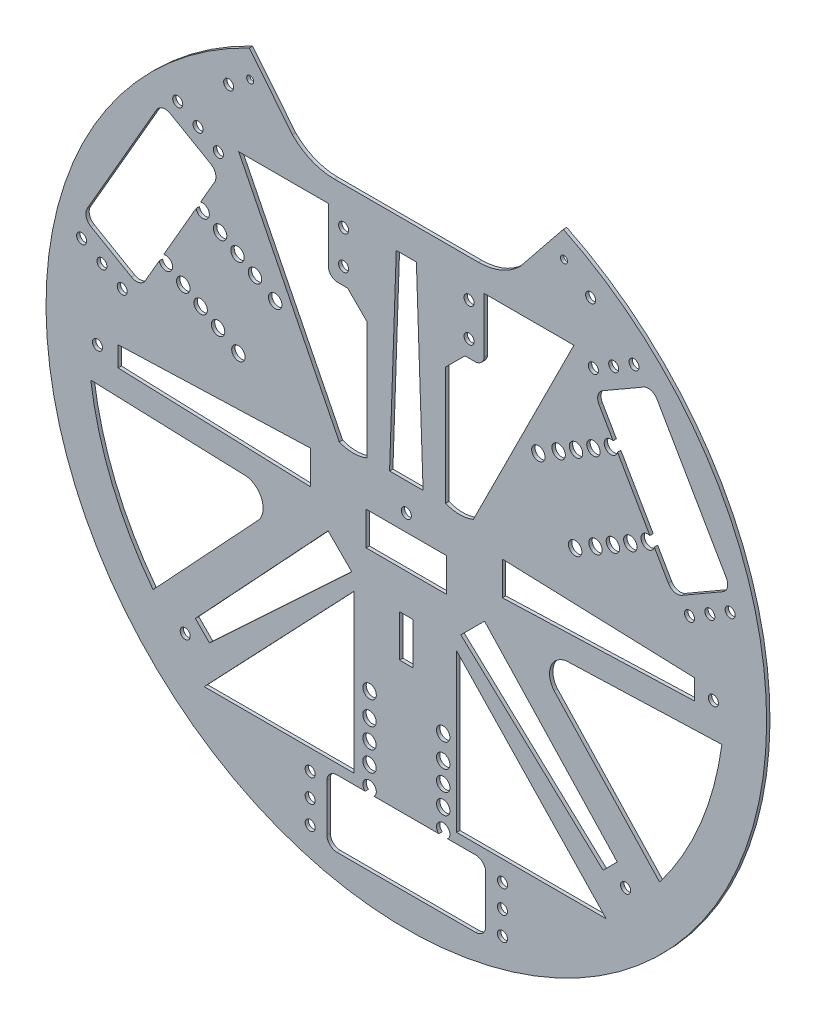
SolidWorks part; units mm, degrees
ref_plane "Alzado" through (0, 0, 0) normal (0, 0, 1) x (1, 0, 0)
ref_plane "Planta" through (0, 0, 0) normal (0, 1, 0) x (1, 0, 0)
ref_plane "Vista lateral" through (0, 0, 0) normal (1, 0, 0) x (0, 0, -1)
sketch "Croquis1" plane through (0, 0, 0) normal (0, 0, 1) x (1, 0, 0)
  line L0 (88.1804, 90.3547) -> (131.1804, 90.3547)
  line L1 (62.8222, 111.5324) -> (75.6804, 95.5324)
  line L2 (156.5385, 111.5324) -> (143.6804, 95.5324)
  line L3 (172.6809, 62.0147) -> (182.3396, 45.2852)
  line L4 (171.3574, 64.3071) -> (167.1578, 71.5807)
  line L5 (168.2559, 75.6788) -> (180.3802, 82.6788)
  line L6 (184.4783, 81.5807) -> (205.161, 45.7571)
  line L7 (191.9386, 34.6591) -> (204.063, 41.6591)
  line L8 (183.6625, 42.9938) -> (187.8405, 35.7571)
  line L9 (35.9673, 43.1072) -> (31.7885, 35.8697)
  line L10 (27.6904, 34.7716) -> (15.5661, 41.7716)
  line L11 (14.468, 45.8697) -> (35.1518, 81.6951)
  line L12 (51.3742, 75.7932) -> (39.2499, 82.7932)
  line L13 (48.2723, 64.4204) -> (52.4723, 71.6951)
  line L14 (37.2902, 45.3985) -> (46.9489, 62.1281)
  line L15 (122.007, -63.2174) -> (130.3643, -63.2176)
  line L16 (133.3643, -66.2176) -> (133.3643, -80.2176)
  line L17 (88.9967, -83.2176) -> (130.3643, -83.2176)
  line L18 (85.9967, -66.2176) -> (85.9967, -80.2176)
  line L19 (97.3967, -63.2176) -> (88.9967, -63.2176)
  line L20 (119.3613, -63.2174) -> (100.0437, -63.2175)
  line L21 (15.5352, 2.0665) -> (61.8949, 0.4495)
  line L22 (34.1166, -42.7947) -> (65.6128, -9.0435)
  line L23 (185.2441, -42.7947) -> (153.748, -9.0435)
  line L24 (203.8255, 2.0665) -> (157.4659, 0.4495)
  line L25 (111.6804, -11.7176) -> (107.6804, -11.7176)
  line L26 (111.6804, -24.2176) -> (111.6804, -11.7176)
  line L27 (107.6804, -24.2176) -> (111.6804, -24.2176)
  line L28 (107.6804, -24.2176) -> (107.6804, -11.7176)
  line L29 (121.6804, 9.7824) -> (97.6804, 9.7824)
  line L30 (121.6804, -0.2176) -> (121.6804, 9.7824)
  line L31 (97.6804, -0.2176) -> (121.6804, -0.2176)
  line L32 (97.6804, 9.7824) -> (97.6804, -0.2176)
  line L33 (93.9967, -60.2176) -> (93.9967, -13.295)
  line L34 (49.3691, -60.2176) -> (93.9967, -60.2176)
  line L35 (49.3691, -60.2176) -> (93.9967, -13.295)
  line L36 (159.6804, 83.1462) -> (129.6804, 23.1462)
  line L37 (104.6804, 23.1462) -> (114.6804, 23.1462)
  line L38 (106.6804, 81.1462) -> (104.6804, 23.1462)
  line L39 (106.6804, 81.1462) -> (112.6804, 81.1462)
  line L40 (112.6804, 81.1462) -> (114.6804, 23.1462)
  line L41 (93.4169, -8.5521) -> (86.3458, -1.4811)
  line L42 (50.9361, -48.1501) -> (93.4169, -8.5521)
  line L46 (46.7479, -43.9075) -> (50.9361, -48.1501)
  line L47 (86.3458, -1.4811) -> (46.7479, -43.9075)
  line L48 (81.0201, 17.2596) -> (23.6804, 15.2824)
  line L49 (81.0201, 17.2596) -> (81.0201, 7.2824)
  line L50 (23.6804, 9.2824) -> (81.0201, 7.2824)
  line L51 (23.6804, 15.2824) -> (23.6804, 9.2824)
  line L79 (125.9438, -8.5521) -> (168.3702, -48.1501)
  line L100 (133.0149, -1.4811) -> (125.9438, -8.5521)
  line L104 (172.6129, -43.9075) -> (133.0149, -1.4811)
  line L105 (168.3702, -48.1501) -> (172.6129, -43.9075)
  line L106 (195.6763, 9.2238) -> (195.6763, 15.2238)
  line L107 (195.6763, 9.2238) -> (138.3365, 7.2238)
  line L108 (138.3365, 17.2238) -> (138.3365, 7.2238)
  line L109 (195.6763, 15.2238) -> (138.3365, 17.2238)
  line L110 (59.6804, 83.1462) -> (89.6804, 23.1462)
  line L111 (124.6805, -60.2176) -> (124.6805, -13.295)
  line L112 (124.6805, -13.295) -> (169.308, -60.2176)
  line L113 (124.6805, -60.2176) -> (169.308, -60.2176)
  line L114 (121.4204, 58.3962) -> (121.4204, 23.1462)
  line L115 (97.9204, 58.3962) -> (97.9204, 23.1462)
  line L116 (132.9204, 83.1462) -> (132.9204, 66.7417)
  line L117 (130.3249, 64.1462) -> (127.1704, 64.1462)
  line L118 (86.4204, 83.1462) -> (86.4204, 66.7523)
  line L119 (89.0264, 64.1462) -> (92.1704, 64.1462)
  line L120 (159.6804, 83.1462) -> (132.9204, 83.1462)
  line L121 (86.4204, 83.1462) -> (59.6804, 83.1462)
  line L122 (121.4204, 58.3962) -> (127.1704, 64.1462)
  line L123 (97.9204, 58.3962) -> (92.1704, 64.1462)
  line L124 (130.3249, 64.1462) -> (129.9204, 64.1462)
  circle A0 centre (56.6804, 98.9778) radius 1.5
  arc A1 (131.1804, 90.3547) -> (143.6804, 95.5324) centre (131.1804, 108.0324) ccw
  arc A2 (75.6804, 95.5324) -> (88.1804, 90.3547) centre (88.1804, 108.0324) ccw
  arc A3 (62.8222, 111.5324) -> (156.5385, 111.5324) centre (109.6804, 14.7824) ccw
  circle A4 centre (200.2327, 33.9415) radius 1.5
  circle A5 centre (171.5489, 83.6233) radius 1.5
  circle A6 centre (138.3643, -73.2176) radius 1.5
  circle A7 centre (80.9967, -73.2176) radius 1.5
  circle A8 centre (18.8602, 33.8289) radius 1.5
  circle A9 centre (47.5429, 83.5089) radius 1.5
  circle A10 centre (109.6804, 14.7824) radius 1.5
  circle A11 centre (156.7178, 103.8079) radius 1.05
  circle A12 centre (63.0981, 103.4945) radius 1.05
  circle A13 centre (175.1093, -49.332) radius 1.5
  circle A14 centre (43.7132, -49.332) radius 1.5
  circle A15 centre (201.2939, 12.168) radius 1.5
  circle A16 centre (17.5287, 12.168) radius 1.5
  circle A17 centre (206.2949, 37.4415) radius 1.5
  circle A18 centre (194.1706, 30.4415) radius 1.5
  circle A19 centre (177.6111, 87.1233) radius 1.5
  circle A20 centre (165.4868, 80.1233) radius 1.5
  circle A21 centre (24.9224, 30.3289) radius 1.5
  circle A22 centre (12.798, 37.3289) radius 1.5
  circle A23 centre (53.6051, 80.0089) radius 1.5
  circle A24 centre (41.4808, 87.0089) radius 1.5
  circle A25 centre (138.3643, -66.332) radius 1.5
  circle A26 centre (80.9967, -66.332) radius 1.5
  circle A27 centre (80.9967, -80.2176) radius 1.5
  circle A28 centre (138.3643, -80.2176) radius 1.5
  circle A29 centre (166.1135, 34.3896) radius 2
  circle A30 centre (171.3096, 37.3896) radius 2
  circle A31 centre (155.1118, 53.4454) radius 2
  circle A32 centre (160.3079, 56.4454) radius 2
  circle A33 centre (176.5058, 40.3895) radius 2
  circle A34 centre (165.5041, 59.4453) radius 2
  arc A35 (182.3396, 45.2852) -> (183.6625, 42.9938) centre (181.702, 43.3895) ccw
  arc A36 (171.3574, 64.3071) -> (172.6809, 62.0147) centre (170.7206, 62.4112) ccw
  arc A37 (168.2559, 75.6788) -> (167.1578, 71.5807) centre (169.7559, 73.0807) ccw
  arc A38 (184.4783, 81.5807) -> (180.3802, 82.6788) centre (181.8802, 80.0807) ccw
  arc A39 (204.063, 41.6591) -> (205.161, 45.7571) centre (202.563, 44.2571) ccw
  arc A40 (187.8405, 35.7571) -> (191.9386, 34.6591) centre (190.4386, 37.2571) ccw
  circle A41 centre (160.0499, 30.8931) radius 2
  circle A42 centre (149.0699, 49.9113) radius 2
  circle A43 centre (53.5163, 34.503) radius 2
  circle A44 centre (48.3201, 37.5029) radius 2
  circle A45 centre (64.518, 53.5588) radius 2
  circle A46 centre (59.3218, 56.5587) radius 2
  circle A47 centre (43.1239, 40.5029) radius 2
  circle A48 centre (54.1256, 59.5587) radius 2
  arc A49 (35.9673, 43.1072) -> (37.2902, 45.3985) centre (37.9278, 43.5029) ccw
  arc A50 (27.6904, 34.7716) -> (31.7885, 35.8697) centre (29.1904, 37.3697) ccw
  arc A51 (14.468, 45.8697) -> (15.5661, 41.7716) centre (17.0661, 44.3697) ccw
  arc A52 (39.2499, 82.7932) -> (35.1518, 81.6951) centre (37.7499, 80.1951) ccw
  arc A53 (52.4723, 71.6951) -> (51.3742, 75.7932) centre (49.8742, 73.1951) ccw
  arc A54 (46.9489, 62.1281) -> (48.2723, 64.4204) centre (48.9092, 62.5245) ccw
  circle A55 centre (59.5799, 31.0064) radius 2
  circle A56 centre (70.5599, 50.0247) radius 2
  circle A57 centre (120.684, -43.7174) radius 2
  circle A58 centre (120.684, -49.7174) radius 2
  circle A59 centre (98.6804, -43.7176) radius 2
  circle A60 centre (98.6804, -49.7176) radius 2
  circle A61 centre (120.6841, -55.7174) radius 2
  circle A62 centre (98.6804, -55.7176) radius 2
  arc A63 (122.007, -63.2174) -> (119.3613, -63.2174) centre (120.6841, -61.7174) ccw
  arc A64 (133.3643, -66.2176) -> (130.3643, -63.2176) centre (130.3643, -66.2176) ccw
  arc A65 (130.3643, -83.2176) -> (133.3643, -80.2176) centre (130.3643, -80.2176) ccw
  arc A66 (85.9967, -80.2176) -> (88.9967, -83.2176) centre (88.9967, -80.2176) ccw
  arc A67 (88.9967, -63.2176) -> (85.9967, -66.2176) centre (88.9967, -66.2176) ccw
  arc A68 (100.0437, -63.2175) -> (97.3967, -63.2176) centre (98.7202, -61.7181) ccw
  circle A69 centre (120.6803, -36.7179) radius 2
  circle A70 centre (98.72, -36.7181) radius 2
  arc A71 (15.5352, 2.0665) -> (34.1166, -42.7947) centre (109.6804, 14.7824) ccw
  arc A72 (65.6128, -9.0435) -> (61.8949, 0.4495) centre (61.1389, -5.3211) ccw
  arc A73 (185.2441, -42.7947) -> (203.8255, 2.0665) centre (109.6804, 14.7824) ccw
  arc A74 (157.4659, 0.4495) -> (153.748, -9.0435) centre (158.2218, -5.3211) ccw
  circle A110 centre (164.6804, 97.9778) radius 1.5
  circle A111 centre (128.3987, 79.1566) radius 1.5
  circle A112 centre (128.3987, 69.1566) radius 1.5
  circle A113 centre (90.9621, 79.1566) radius 1.5
  circle A114 centre (90.9621, 69.1566) radius 1.5
  arc A115 (121.4204, 23.1462) -> (129.6804, 23.1462) centre (125.5504, 33.3962) ccw
  arc A151 (89.6804, 23.1462) -> (97.9204, 23.1462) centre (93.8004, 33.3962) ccw
  arc A152 (129.9204, 64.1462) -> (132.9204, 67.1462) centre (130.1227, 66.944) ccw
  arc A153 (86.4204, 67.1462) -> (89.0264, 64.1462) centre (89.2234, 66.9493) ccw
extrude "Saliente-Extruir1" add sketch "Croquis1" along normal blind 1 contours L1 A3 L2 A1 L0 A2 A114 A113 A112 A111 A110 A74 L24 A73 L23 A72 L22 A71 L21 A70 A69 A68 L20 A63 L15 A64 L16 A65 L17 A66 L18 A67 L19 A62 A61 A60 A59
